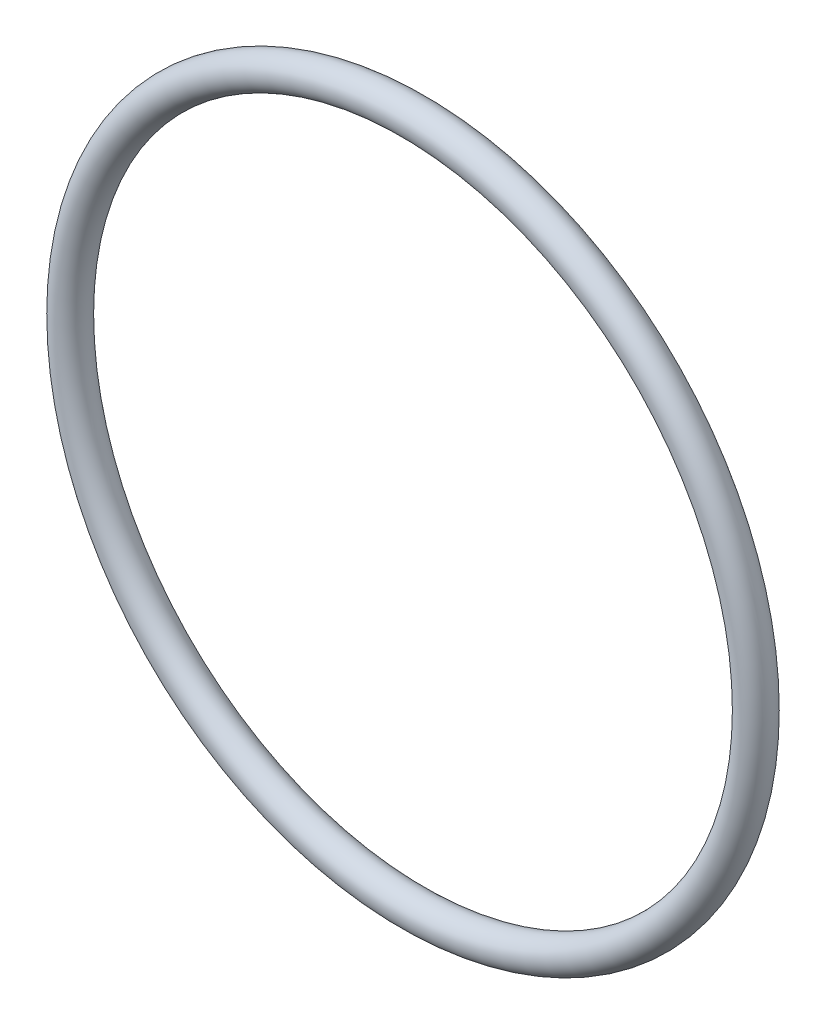
SolidWorks part; units mm, degrees
ref_plane "Front" through (0, 0, 0) normal (0, 0, 1) x (1, 0, 0)
ref_plane "Top" through (0, 0, 0) normal (0, 1, 0) x (1, 0, 0)
ref_plane "Right" through (0, 0, 0) normal (1, 0, 0) x (0, 0, -1)
sketch "Sketch1" plane through (0, 0, 0) normal (1, 0, 0) x (0, -1, 0)
  line L0 (0, -1.7653) -> (0, 1.7653) construction
  line L2 (-42.0776, 0) -> (42.0776, 0) construction
  line L3 (-34.7218, 0) -> (34.7218, 0) construction
  circle A0 centre (36.4871, 0) radius 1.7653
  point P9 (34.7218, 0)
  point P10 (38.2524, 0)
  point P13 (36.4871, 1.7653)
  point P14 (36.4871, -1.7653)
  dimension "Width" = 3.5306
  dimension "ID" = 69.4436
revolve "Revolve1" add sketch "Sketch1" angle 360 about L0
ref_plane "Plane1" through (0, 0, 1.7653) normal (0, 0, 1) x (1, 0, 0)
sketch "Sketch2" plane through (0, 0, 1.7653) normal (0, 0, 1) x (1, 0, 0)
  circle A0 centre (0, 0) radius 36.4871
ref_plane "Plane2" through (0, -36.4871, 1.7653) normal (0, 0, 1) x (1, 0, 0)
sketch "Sketch3" plane through (0, -36.4871, 1.7653) normal (0, 0, 1) x (1, 0, 0)
  circle A0 centre (0, 36.4871) radius 36.4871
